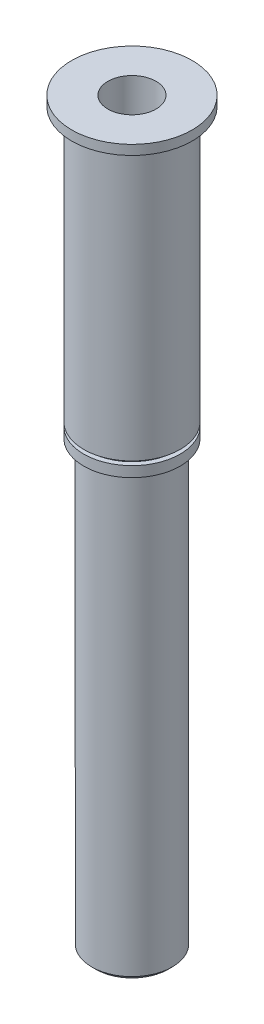
SolidWorks part; units mm, degrees
material "AISI 304"
ref_plane "Front" through (0, 0, 0) normal (0, 0, 1) x (1, 0, 0)
ref_plane "Top" through (0, 0, 0) normal (0, 1, 0) x (1, 0, 0)
ref_plane "Right" through (0, 0, 0) normal (1, 0, 0) x (0, 0, -1)
sketch "Sketch1" plane through (0, 0, 0) normal (0, 0, 1) x (1, 0, 0)
  line L0 (0, 54.4532) -> (0, -60.4732) construction
  line L1 (-3, 39.9339) -> (-3, 14.9339)
  line L2 (-6, 39.9339) -> (-6, 2.9339)
  line L3 (-6, 2.9339) -> (-5, 2.9339)
  line L4 (-5, 2.9339) -> (-5, -52.0661)
  line L5 (-5, -52.0661) -> (0, -52.0661)
  line L6 (-3, 14.9339) -> (0, 14.9339)
  line L7 (-3, 39.9339) -> (-6, 39.9339)
  line L8 (0, -52.0661) -> (0, 14.9339)
  dimension "D1" = 6
  dimension "D2" = 12
  dimension "D3" = 10
  dimension "D4" = 25
  dimension "D5" = 37
  dimension "D6" = 55
revolve "Revolve1" add sketch "Sketch1" angle 360 about L0
chamfer "Chamfer1" distance 0.5 angle 45 1 edges at (0, -52.0661, 5)
sketch "Sketch2" plane through (0, 39.9339, 0) normal (0, 1, 0) x (1, 0, 0)
  circle A1 centre (0, 0) radius 3 construction
  circle A2 centre (0, 0) radius 7.5
  circle A3 centre (0, 0) radius 7.5
  circle A4 centre (0, 0) radius 3
  dimension "D1" = 1.5
extrude "Boss-Extrude1" add sketch "Sketch2" against normal blind 1.2
ref_plane "Plane1" through (0, 54.4532, 0) normal (-1, 0, 0) x (0, 0, 1)
sketch "Sketch4" plane through (0, 54.4532, 0) normal (-1, 0, 0) x (0, 0, 1)
  line L0 (6.225, -50.2194) -> (5.4, -50.2194)
  line L1 (5.4, -50.2194) -> (5.4, -49.7194)
  line L2 (5.4, -49.7194) -> (6.225, -49.7194)
  line L3 (6.325, -49.8194) -> (6.325, -50.1194)
  line L4 (0, -50) -> (0, 50) construction
  line L6 (-6, -51.5194) -> (6, -51.5194) construction
  arc A0 (6.325, -50.1194) -> (6.225, -50.2194) centre (6.225, -50.1194) cw
  arc A1 (6.325, -49.8194) -> (6.225, -49.7194) centre (6.225, -49.8194) ccw
  dimension "D1" = 0.1
  dimension "D2" = 0.1
  dimension "D4" = 0.5
  dimension "D5" = 1.3
revolve "Groove for ANSI B27.7 - 3BM1-12, Basic Internal Retaining Ring1" cut sketch "Sketch4"
sketch "Sketch5" plane through (0, 0, 0) normal (1, 0, 0) x (0, 0, -1)
  line L0 (7.5, 39.9339) -> (-7.5, 39.9339) construction
  circle A0 centre (0, 24.9339) radius 2.5
  dimension "D2" = 5
  dimension "D1" = 15
extrude "Cut-Extrude1" cut sketch "Sketch5" against normal through all
hole_wizard "M6 Tapped Hole1" positions "Sketch7" profile "Sketch6" tap size "M6" standard "IS"
sketch "Sketch7" plane through (0, -52.0661, 0) normal (0, -1, 0) x (1, 0, 0)
  circle A0 centre (0, 0) radius 4.5 construction
  point P0 (0, 0)
sketch "Sketch6" plane through (0, -52.0661, 0) normal (1, 0, 0) x (0, 0, -1)
  line L0 (0, 0) -> (0, 18.5022)
  line L1 (0, 18.5022) -> (2.5, 17)
  line L2 (2.5, 17) -> (2.5, 0)
  line L5 (2.5, 0) -> (0, 0)
  line L10 (0, 18.5022) -> (-2.5, 17) construction
  line L11 (0, -6.35) -> (0, 107.95) construction
  dimension "Tap Drill Dia." = 5
  dimension "Tap Drill Depth" = 17
  dimension "Drill Angle" = 118
cosmetic thread "Hole Thread1" parameters "D1"=12, "D2"=6
